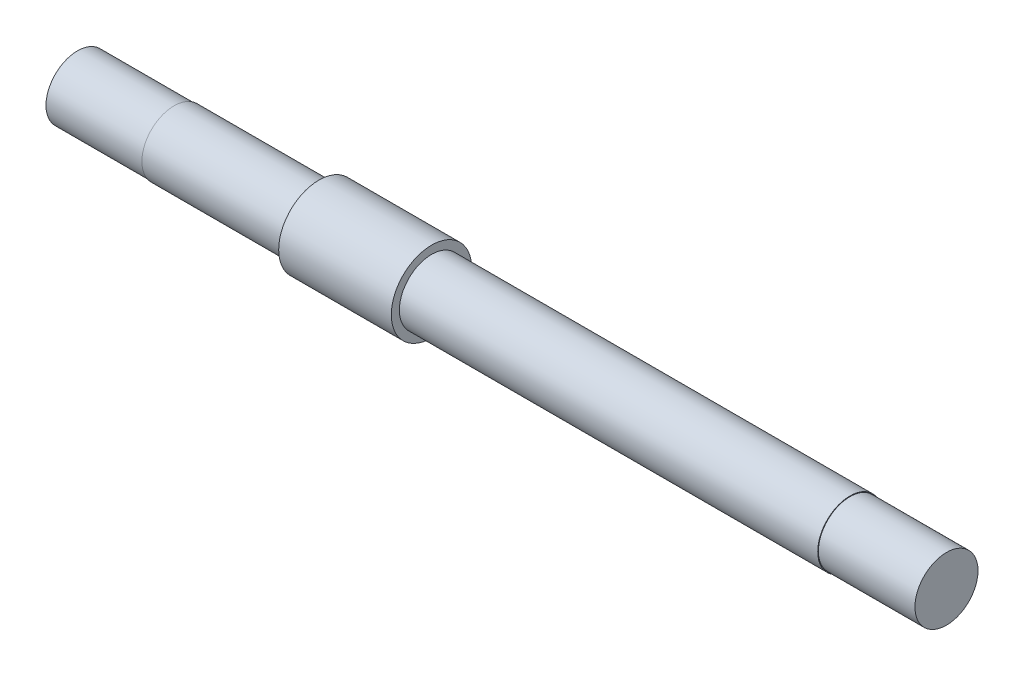
SolidWorks part; units mm, degrees
ref_plane "Front Plane" through (0, 0, 0) normal (0, 0, 1) x (1, 0, 0)
ref_plane "Top Plane" through (0, 0, 0) normal (0, 1, 0) x (1, 0, 0)
ref_plane "Right Plane" through (0, 0, 0) normal (1, 0, 0) x (0, 0, -1)
sketch "Sketch1" plane through (0, 0, 0) normal (1, 0, 0) x (0, 0, -1)
  circle A0 centre (0, 0) radius 6.35
  dimension "D1" = 12.7
extrude "Boss-Extrude1" add sketch "Sketch1" along normal mid plane 31.75
sketch "Sketch2" plane through (-15.875, 0, 0) normal (-1, 0, 0) x (0, 0, 1)
  circle A0 centre (0, 0) radius 7.9375
  dimension "D1" = 15.875
extrude "Boss-Extrude2" add sketch "Sketch2" along normal blind 22.225
sketch "Sketch3" plane through (15.875, 0, 0) normal (1, 0, 0) x (0, 0, -1)
  circle A0 centre (0, 0) radius 6.35
  dimension "D1" = 12.7
extrude "Boss-Extrude3" add sketch "Sketch3" along normal blind 69.85
sketch "Sketch4" plane through (-38.1, 0, 0) normal (-1, 0, 0) x (0, 0, 1)
  circle A0 centre (0, 0) radius 6.35
  dimension "D1" = 12.7
extrude "Boss-Extrude4" add sketch "Sketch4" along normal blind 47.625
sketch "Sketch5" plane through (-85.725, 0, 0) normal (-1, 0, 0) x (0, 0, 1)
  circle A0 centre (0, 0) radius 6.223
  dimension "D1" = 12.446
sketch "Sketch6" plane through (85.725, 0, 0) normal (1, 0, 0) x (0, 0, -1)
  circle A0 centre (0, 0) radius 6.223
  dimension "D1" = 12.446
extrude "Cut-Extrude3" cut sketch "Sketch5" against normal blind 19.05 flip side to cut
extrude "Cut-Extrude4" cut sketch "Sketch6" against normal blind 19.05 flip side to cut
